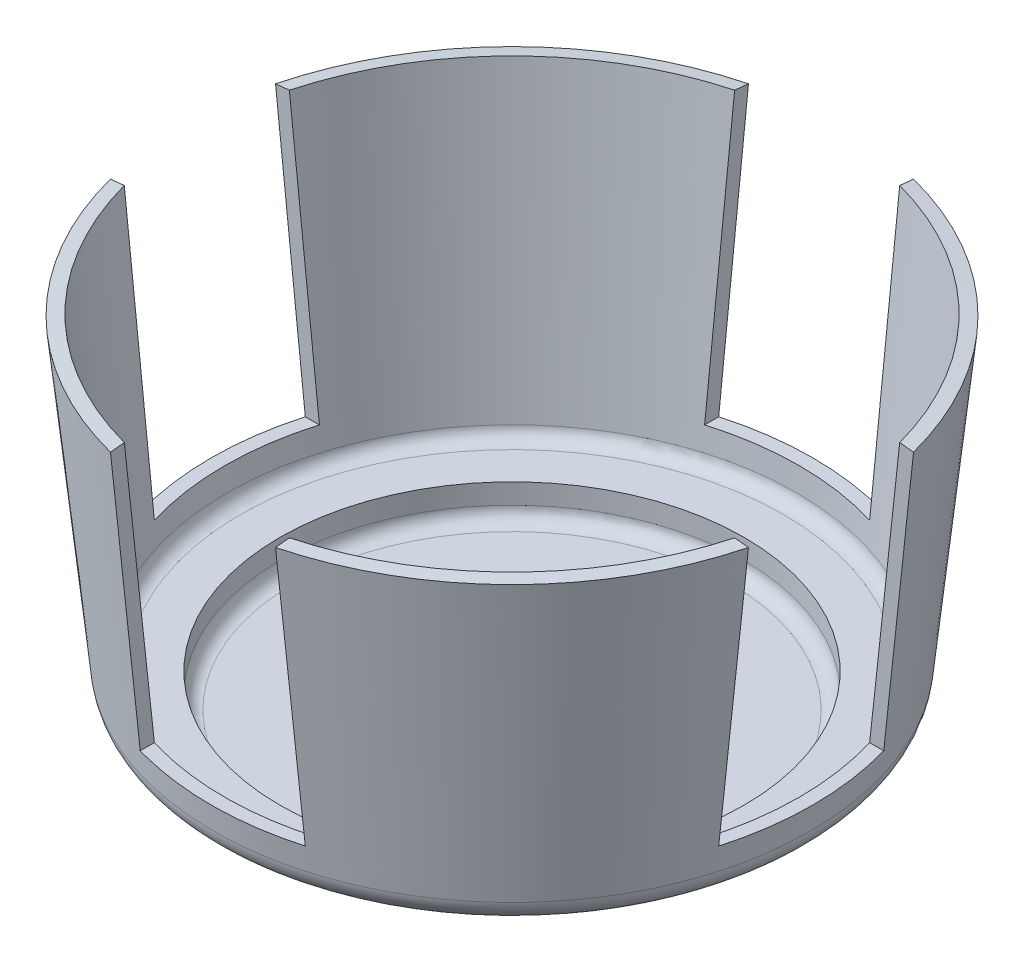
SolidWorks part; units mm, degrees
ref_plane "Front Plane" through (0, 0, 0) normal (0, 0, 1) x (1, 0, 0)
ref_plane "Top Plane" through (0, 0, 0) normal (0, 1, 0) x (1, 0, 0)
ref_plane "Right Plane" through (0, 0, 0) normal (1, 0, 0) x (0, 0, -1)
sketch "Sketch1" plane through (0, 0, 0) normal (0, 0, 1) x (1, 0, 0)
  line L0 (0, 0) -> (0, 51) construction
  line L1 (0, 0) -> (32.5, 0)
  line L2 (34.5, 2) -> (34.5, 5)
  line L3 (34.5, 5) -> (40.3644, 5)
  line L4 (42.3534, 6.7909) -> (47, 51)
  arc A0 (32.5, 0) -> (34.5, 2) centre (32.5, 2) ccw
  arc A1 (40.3644, 5) -> (42.3534, 6.7909) centre (40.3644, 7) ccw
  point P9 (34.5, 0)
  dimension "D6" = 2
  dimension "D1" = 51
  dimension "D2" = 69
  dimension "D3" = 5
  dimension "D4" = 47
  dimension "D5" = 96
revolve "Revolve-Thin1" add sketch "Sketch1" angle 360 about L0
sketch "Sketch2" plane through (0, 0, 0) normal (0, 0, 1) x (1, 0, 0)
  line L0 (47, 51) -> (-47, 51) construction
  line L1 (-12.27, 51) -> (12.27, 51)
  line L2 (-12.27, 51) -> (-12.27, 10.13)
  line L3 (-12.27, 10.13) -> (12.27, 10.13)
  line L4 (12.27, 51) -> (12.27, 10.13)
  point P6 (0, 51)
  dimension "D1" = 24.54
  dimension "D2" = 40.87
extrude "Cut-Extrude1" cut sketch "Sketch2" along normal up to next
pattern_circular "CirPattern1" count 4 over 360 about axis through (0, 0, 0) along (0, 1, 0) of "Cut-Extrude1"
sketch "Sketch3" plane through (0, -2, 0) normal (0, -1, 0) x (1, 0, 0)
  circle A0 centre (0, 0) radius 21
  dimension "D1" = 42
extrude "Cut-Extrude2" cut sketch "Sketch3" against normal up to next
